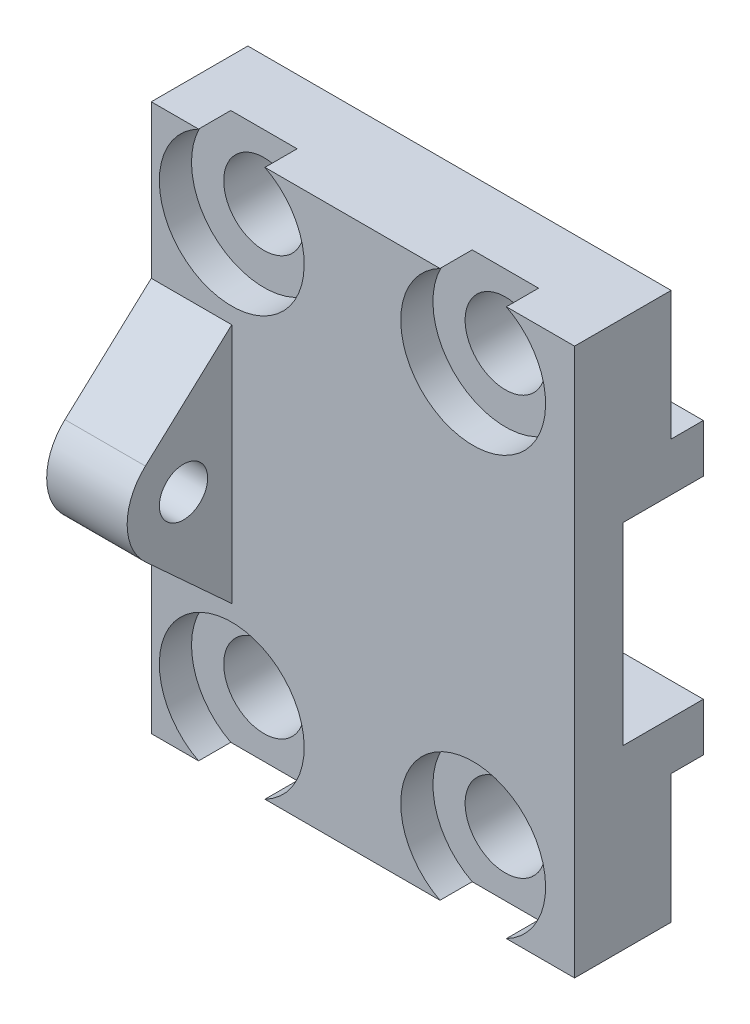
SolidWorks part; units mm, degrees
ref_plane "Front" through (0, 0, 0) normal (0, 0, 1) x (1, 0, 0)
ref_plane "Top" through (0, 0, 0) normal (0, 1, 0) x (1, 0, 0)
ref_plane "Right" through (0, 0, 0) normal (1, 0, 0) x (0, 0, -1)
sketch "Эскиз1" plane through (0, 0, 0) normal (0, 0, 1) x (1, 0, 0)
  line L1 (-12.15, 6) -> (12.15, 6)
  line L2 (-12.15, 6) -> (-12.15, -6)
  line L3 (-12.15, -6) -> (12.15, -6)
  line L4 (12.15, 6) -> (12.15, -6)
  line L5 (-12.15, 6) -> (12.15, -6) construction
  line L6 (-12.15, -6) -> (12.15, 6) construction
  line L7 (-12.15, 9) -> (12.15, 9)
  line L8 (-12.15, 9) -> (-12.15, -9)
  line L9 (-12.15, -9) -> (12.15, -9)
  line L10 (12.15, 9) -> (12.15, -9)
  line L11 (-12.15, 9) -> (12.15, -9) construction
  line L12 (-12.15, -9) -> (12.15, 9) construction
  point P0 (0, 0)
  point P6 (0, 0)
  dimension "D1" = 24.3
  dimension "D2" = 12
  dimension "D3" = 18
extrude "Бобышка-Вытянуть1" add sketch "Эскиз1" along normal blind 5 contours L10 L7 L8 L1 | L10 L3 L8 L9
sketch "Эскиз2" plane through (0, 0, 5) normal (0, 0, 1) x (1, 0, 0)
  line L1 (-12.15, 9) -> (12.15, 9)
  line L2 (-12.15, 9) -> (-12.15, -9)
  line L3 (-12.15, -9) -> (12.15, -9)
  line L4 (12.15, 9) -> (12.15, -9)
extrude "Бобышка-Вытянуть2" add sketch "Эскиз2" along normal blind 3
sketch "Эскиз3" plane through (-12.15, 0, 0) normal (-1, 0, 0) x (0, 0, 1)
  line L0 (0, -9) -> (0, -6)
  line L1 (0, -6) -> (3, -6)
  line L2 (5, -6) -> (0, -6) construction
  line L3 (3, -6) -> (5, -4)
  line L4 (5, 6) -> (5, -6) construction
  line L5 (5, -4) -> (5, 4)
  line L6 (5, 4) -> (3, 6)
  line L7 (5, 6) -> (0, 6) construction
  line L8 (3, 6) -> (0, 6)
  line L9 (0, 6) -> (0, 9)
  line L10 (0, 9) -> (8, 9)
  line L11 (8, 9) -> (8, -9)
  line L12 (8, -9) -> (0, -9)
  dimension "D1" = 2
  dimension "D2" = 2
  dimension "D3" = 2
extrude "Бобышка-Вытянуть3" add sketch "Эскиз3" along normal blind 2 separate body
sketch "Эскиз5" plane through (0, 0, 8) normal (0, 0, 1) x (1, 0, 0)
  line L1 (12.15, -9) -> (-14.15, -9)
  line L2 (12.15, -9) -> (12.15, -17)
  line L3 (12.15, -17) -> (-14.15, -17)
  line L4 (-14.15, -9) -> (-14.15, -17)
  line L5 (12.15, 9) -> (-14.15, 9)
  line L6 (12.15, 9) -> (12.15, 17)
  line L7 (12.15, 17) -> (-14.15, 17)
  line L8 (-14.15, 9) -> (-14.15, 17)
  circle A0 centre (5.85, 13) radius 2.5
  circle A1 centre (-9.15, 13) radius 2.5
  circle A2 centre (-9.15, -13) radius 2.5
  circle A3 centre (5.85, -13) radius 2.5
  dimension "D1" = 5
extrude "Бобышка-Вытянуть5" add sketch "Эскиз5" against normal up to surface (6 mm away)
sketch "Эскиз6" plane through (-14.15, 0, 0) normal (-1, 0, 0) x (0, 0, 1)
  line L0 (8, 17) -> (8, -17) construction
  line L1 (0, -6) -> (0, -9) construction
  line L2 (13.3656, 2.5796) -> (8, 7.5)
  line L3 (13.3656, -2.5796) -> (8, -7.5)
  line L4 (8, 0) -> (14.5, 0) construction
  line L5 (8, 7.5) -> (8, -7.5)
  circle A0 centre (11, 0) radius 1.5
  circle A1 centre (11, 0) radius 3.5
  point P2 (8, 0)
  line M4 (8, -17) -> (8, 17)
  dimension "D1" = 3
  dimension "D3" = 7
  dimension "D2" = 11
  dimension "D4" = 15
extrude "Бобышка-Вытянуть6" add sketch "Эскиз6" against normal blind 5 separate body contours A1 L3 M4 | A1 L2 M4 | L4 A0 A1 M4 | L4 L5 A1 A0
sketch "Эскиз7" plane through (0, 0, 8) normal (0, 0, 1) x (1, 0, 0)
  circle A0 centre (5.85, 13) radius 4.5
  circle A1 centre (5.85, -13) radius 4.5
  circle A2 centre (-9.15, -13) radius 4.5
  circle A3 centre (-9.15, 13) radius 4.5
  dimension "D1" = 9
extrude "Вырез-Вытянуть1" cut sketch "Эскиз7" against normal blind 2
